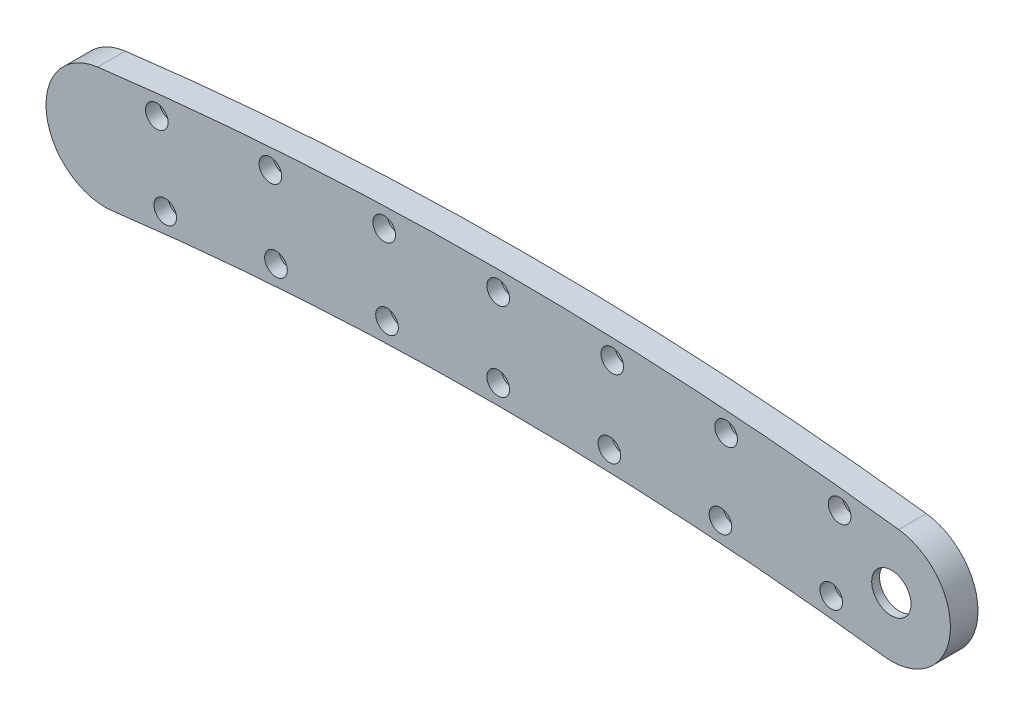
SolidWorks part; units mm, degrees
ref_plane "Front Plane" through (0, 0, 0) normal (0, 0, 1) x (1, 0, 0)
ref_plane "Top Plane" through (0, 0, 0) normal (0, 1, 0) x (1, 0, 0)
ref_plane "Right Plane" through (0, 0, 0) normal (1, 0, 0) x (0, 0, -1)
sketch "Sketch1" plane through (0, 0, 0) normal (0, 0, 1) x (1, 0, 0)
  line L0 (0, 0) -> (0, -5052.3627) construction
  line L1 (0, 0) -> (125, 0) construction
  line L2 (0, 0) -> (0, 40) construction
  arc A0 (125, 0) -> (0, 10) centre (0, -776.25) ccw
  arc A1 (127.3847, 14.8092) -> (0, 25) centre (0, -776.25) ccw
  arc A2 (129.7695, 29.6184) -> (0, 40) centre (0, -776.25) ccw
  circle A3 centre (14.3, 24.8724) radius 13.3
  circle A5 centre (42.8818, 23.8517) radius 13.3
  circle A6 centre (71.4089, 21.8116) radius 13.3
  circle A7 centre (99.8451, 18.7547) radius 13.3
  circle A9 centre (99.8451, 18.7547) radius 15
  arc A10 (-129.7695, 29.6184) -> (0, 40) centre (0, -776.25) cw
  arc A11 (-125, 0) -> (0, 10) centre (0, -776.25) cw
  circle A12 centre (-14.3, 24.8724) radius 13.3
  circle A13 centre (-99.8451, 18.7547) radius 15
  circle A14 centre (-99.8451, 18.7547) radius 13.3
  circle A15 centre (-71.4089, 21.8116) radius 13.3
  circle A16 centre (-42.8818, 23.8517) radius 13.3
  dimension "D5" = 14.3
  dimension "D1" = 125
  dimension "D2" = 10
  dimension "D3" = 30
  dimension "D4" = 15
  dimension "D6" = 28.6
  dimension "D7" = 28.6
  dimension "D8" = 28.6
  dimension "D9" = 30
extrude "Boss-Extrude1" add sketch "Sketch1" along normal blind 5
sketch "Sketch2" plane through (0, 0, 5) normal (0, 0, 1) x (1, 0, 0)
  arc A8 (101.7143, 33.6378) -> (-101.7143, 33.6378) centre (0, -776.25) ccw
  arc A9 (-101.7143, 33.6378) -> (-97.9759, 3.8716) centre (-99.8451, 18.7547) ccw
  arc A10 (97.9759, 3.8716) -> (-97.9759, 3.8716) centre (0, -776.25) ccw
  arc A11 (97.9759, 3.8716) -> (101.7143, 33.6378) centre (99.8451, 18.7547) ccw
  arc A12 (101.7143, 33.6378) -> (-101.7143, 33.6378) centre (0, -776.25) ccw
  arc A13 (-101.7143, 33.6378) -> (-97.9759, 3.8716) centre (-99.8451, 18.7547) ccw
  arc A14 (97.9759, 3.8716) -> (-97.9759, 3.8716) centre (0, -776.25) ccw
  arc A15 (97.9759, 3.8716) -> (101.7143, 33.6378) centre (99.8451, 18.7547) ccw
  dimension "D1" = 0
extrude "Boss-Extrude2" add sketch "Sketch2" along normal blind 2
sketch "Sketch3" plane through (0, 0, 0) normal (0, 0, -1) x (-1, 0, 0)
  arc A2 (99.222, 13.7937) -> (-99.222, 13.7937) centre (0, -776.25) ccw
  arc A3 (99.222, 13.7937) -> (-99.222, 13.7937) centre (0, -776.25) ccw
  arc A5 (100.4682, 23.7158) -> (-100.4682, 23.7158) centre (0, -776.25) ccw
  arc A6 (100.4682, 23.7158) -> (-100.4682, 23.7158) centre (0, -776.25) ccw
  arc A10 (101.7143, 33.6378) -> (-101.7143, 33.6378) centre (0, -776.25) ccw
  arc A11 (-101.7143, 33.6378) -> (-97.9759, 3.8716) centre (-99.8451, 18.7547) ccw
  arc A12 (97.9759, 3.8716) -> (-97.9759, 3.8716) centre (0, -776.25) ccw
  arc A13 (97.9759, 3.8716) -> (101.7143, 33.6378) centre (99.8451, 18.7547) ccw
  arc A14 (101.7143, 33.6378) -> (-101.7143, 33.6378) centre (0, -776.25) ccw
  arc A15 (-101.7143, 33.6378) -> (-97.9759, 3.8716) centre (-99.8451, 18.7547) ccw
  arc A16 (97.9759, 3.8716) -> (-97.9759, 3.8716) centre (0, -776.25) ccw
  arc A17 (97.9759, 3.8716) -> (101.7143, 33.6378) centre (99.8451, 18.7547) ccw
  circle M7 centre (-99.8451, 18.7547) radius 13.3
  circle M8 centre (-71.4089, 21.8116) radius 13.3
  circle M9 centre (-42.8818, 23.8517) radius 13.3
  circle M10 centre (-14.3, 24.8724) radius 13.3
  circle M11 centre (71.4089, 21.8116) radius 13.3
  circle M12 centre (14.3, 24.8724) radius 13.3
  circle M17 centre (42.8818, 23.8517) radius 13.3
  circle M18 centre (99.8451, 18.7547) radius 13.3
  dimension "D1" = 10
  dimension "D2" = 20
  dimension "D3" = 0
extrude "Cut-Extrude1" cut sketch "Sketch3" against normal blind 5 contours A6 A3 M8 M7 | A6 A3 M9 M8 | A6 A3 M10 M9 | A6 A3 M12 M10 | A6 A3 M17 M12 | A6 A3 M11 M17 | A6 A3 M18 M11
sketch "Sketch4" plane through (0, 0, 5) normal (0, 0, -1) x (-1, 0, 0)
  circle A0 centre (-99.8451, 18.7547) radius 5
extrude "Cut-Extrude2" cut sketch "Sketch4" against normal blind 5
sketch "Sketch5" plane through (0, 0, 0) normal (0, 0, -1) x (-1, 0, 0)
  line L0 (-85.1062, 15.4387) -> (-86.1751, 25.3814) construction
  line L1 (-56.7978, 17.9717) -> (-57.5111, 27.9462) construction
  line L2 (-28.417, 19.4928) -> (-28.7739, 29.4864) construction
  line L3 (0, 20) -> (0, 30) construction
  line L4 (0, 30) -> (0, 43.7917) construction
  line L5 (-85.1062, 15.4387) -> (-84.1659, 6.6918)
  line L6 (-56.7978, 17.9717) -> (-55.8681, 4.9718) construction
  line L7 (-28.417, 19.4928) -> (-27.9225, 5.6458) construction
  line L8 (0, 20) -> (0, 0) construction
  arc A2 (-84.1593, 25.5955) -> (-88.1903, 25.1622) centre (0, -776.25) ccw construction
  arc A3 (98.599, 8.8327) -> (-98.599, 8.8327) centre (0, -776.25) ccw
  circle A4 centre (-86.7095, 30.3528) radius 1.775
  arc A5 (101.0912, 28.6768) -> (-101.0912, 28.6768) centre (0, -776.25) ccw
  arc A6 (101.0912, 28.6768) -> (-101.0912, 28.6768) centre (0, -776.25) ccw
  arc A7 (-83.1915, 15.6422) -> (-87.0205, 15.2306) centre (0, -776.25) ccw construction
  arc A8 (-54.877, 18.1067) -> (-58.7183, 17.832) centre (0, -776.25) ccw construction
  arc A9 (-26.4926, 19.5592) -> (-30.3412, 19.4217) centre (0, -776.25) ccw construction
  arc A10 (1.9255, 19.9977) -> (-1.9255, 19.9977) centre (0, -776.25) ccw construction
  arc A11 (2.0271, 29.9975) -> (-2.0271, 29.9975) centre (0, -776.25) ccw construction
  circle A12 centre (-57.8678, 32.9335) radius 1.775
  circle A13 centre (-28.9523, 34.4832) radius 1.775
  circle A14 centre (0, 35) radius 1.775
  arc A16 (98.599, 8.8327) -> (-98.599, 8.8327) centre (0, -776.25) ccw
  arc A17 (-55.489, 28.0883) -> (-59.5329, 27.7991) centre (0, -776.25) ccw construction
  arc A18 (-26.748, 29.5562) -> (-30.7996, 29.4115) centre (0, -776.25) ccw construction
  circle A20 centre (-84.5718, 10.4673) radius 1.775
  circle A21 centre (-56.4411, 12.9844) radius 1.775
  circle A22 centre (-28.2386, 14.4959) radius 1.775
  circle A23 centre (0, 15) radius 1.775
  circle A24 centre (28.9523, 34.4832) radius 1.775
  circle A25 centre (28.2386, 14.4959) radius 1.775
  circle A26 centre (57.8678, 32.9335) radius 1.775
  circle A27 centre (56.4411, 12.9844) radius 1.775
  circle A28 centre (84.5718, 10.4673) radius 1.775
  circle A29 centre (86.7095, 30.3528) radius 1.775
  point P61 (0, 0)
  point P62 (0, 0)
  dimension "D3" = 3.55
  dimension "D4" = 3.55
  dimension "D5" = 3.55
  dimension "D6" = 3.55
  dimension "D1" = 5
  dimension "D2" = 25
extrude "Cut-Extrude3" cut sketch "Sketch5" against normal blind 7 contours A28 A16 | A28 A16 | A29 | A26 | A27 | A25 | A24 | A14 | A23 | A22 | A13 | A21 | A12 | A4 | A20
sketch "Sketch6" plane through (0, 0, 7) normal (0, 0, 1) x (1, 0, 0)
  circle A84 centre (-86.7095, 30.3528) radius 2.875
  circle A85 centre (-84.5718, 10.4673) radius 2.875
  circle A86 centre (-57.8678, 32.9335) radius 2.875
  circle A87 centre (-56.4411, 12.9844) radius 2.875
  circle A88 centre (-28.9523, 34.4832) radius 2.875
  circle A89 centre (-28.2386, 14.4959) radius 2.875
  circle A90 centre (0, 35) radius 2.875
  circle A91 centre (0, 15) radius 2.875
  circle A92 centre (28.9523, 34.4832) radius 2.875
  circle A93 centre (28.2386, 14.4959) radius 2.875
  circle A94 centre (57.8678, 32.9335) radius 2.875
  circle A95 centre (56.4411, 12.9844) radius 2.875
  circle A96 centre (86.7095, 30.3528) radius 2.875
  circle A99 centre (84.5718, 10.4673) radius 2.875
  point P2 (-84.5718, 10.4673)
  point P5 (-57.8678, 32.9335)
  point P8 (-56.4411, 12.9844)
  point P11 (-28.9523, 34.4832)
  point P14 (-28.2386, 14.4959)
  point P17 (0, 35)
  point P20 (0, 15)
  point P23 (28.9523, 34.4832)
  point P26 (28.2386, 14.4959)
  point P30 (57.8678, 32.9335)
  point P33 (56.4411, 12.9844)
  point P36 (86.7095, 30.3528)
  point P39 (84.5718, 8.6923)
  point P40 (84.5718, 10.4673)
  point P42 (83.5987, 8.9829)
  point P43 (86.0521, 11.4468)
extrude "Cut-Extrude4" cut sketch "Sketch6" against normal blind 3.6
equation "\"125mmm\"=0.00229714"
